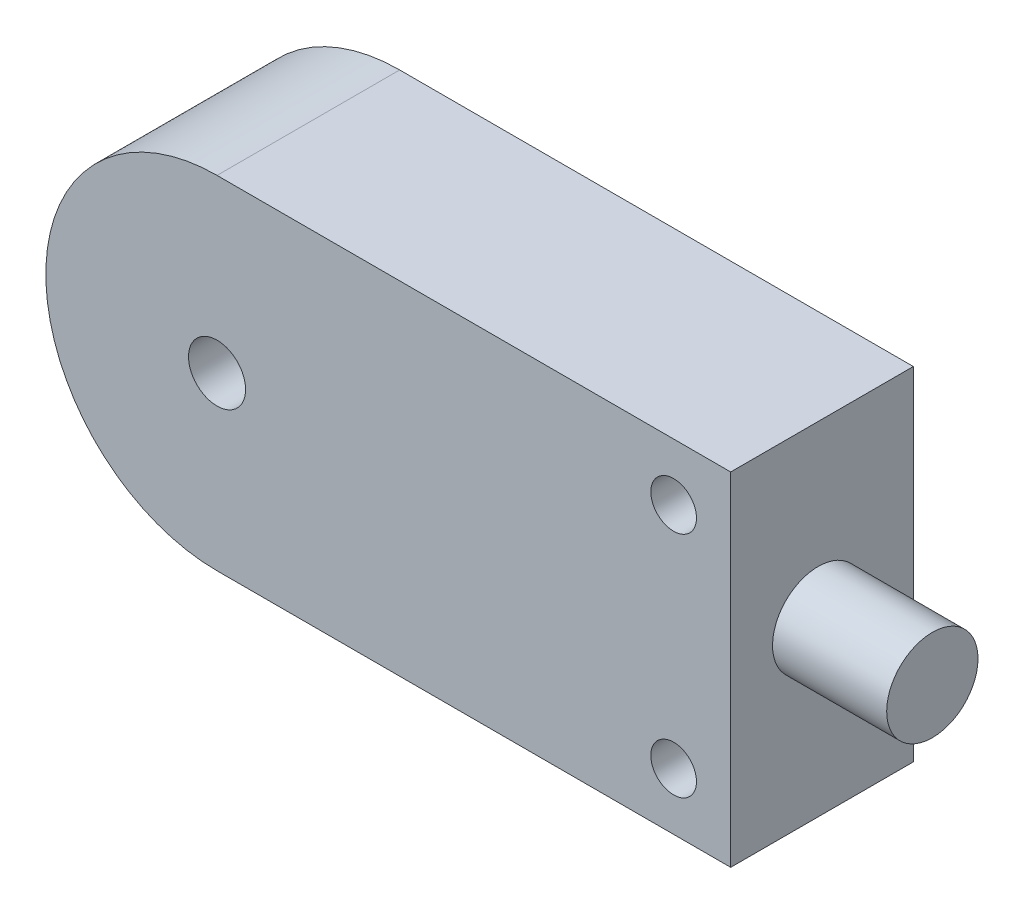
SolidWorks part; units mm, degrees
ref_plane "Front" through (0, 0, 0) normal (0, 0, 1) x (1, 0, 0)
ref_plane "Top" through (0, 0, 0) normal (0, 1, 0) x (1, 0, 0)
ref_plane "Right" through (0, 0, 0) normal (1, 0, 0) x (0, 0, -1)
sketch "Sketch1" plane through (0, 0, 0) normal (0, 0, 1) x (1, 0, 0)
  line L0 (40, 10) -> (40, -10) construction
  line L1 (0, 15) -> (45, 15)
  line L2 (0, 0) -> (40, 0) construction
  line L3 (0, -15) -> (45, -15)
  line L4 (45, 15) -> (45, -15)
  arc A0 (0, 15) -> (0, -15) centre (0, 0) ccw
  circle A1 centre (40, 10) radius 2
  circle A2 centre (40, -10) radius 2
  circle A3 centre (0, 0) radius 2.5
  dimension "D1" = 30
  dimension "D2" = 45
  dimension "D4" = 4
  dimension "D6" = 5
  dimension "D3" = 5
  dimension "D5" = 20
extrude "Boss-Extrude1" add sketch "Sketch1" along normal blind 16
sketch "Sketch2" plane through (45, 0, 0) normal (1, 0, 0) x (0, 0, -1)
  circle A0 centre (-8.3341, 0) radius 4
  dimension "D1" = 8
extrude "Boss-Extrude2" add sketch "Sketch2" along normal blind 10
